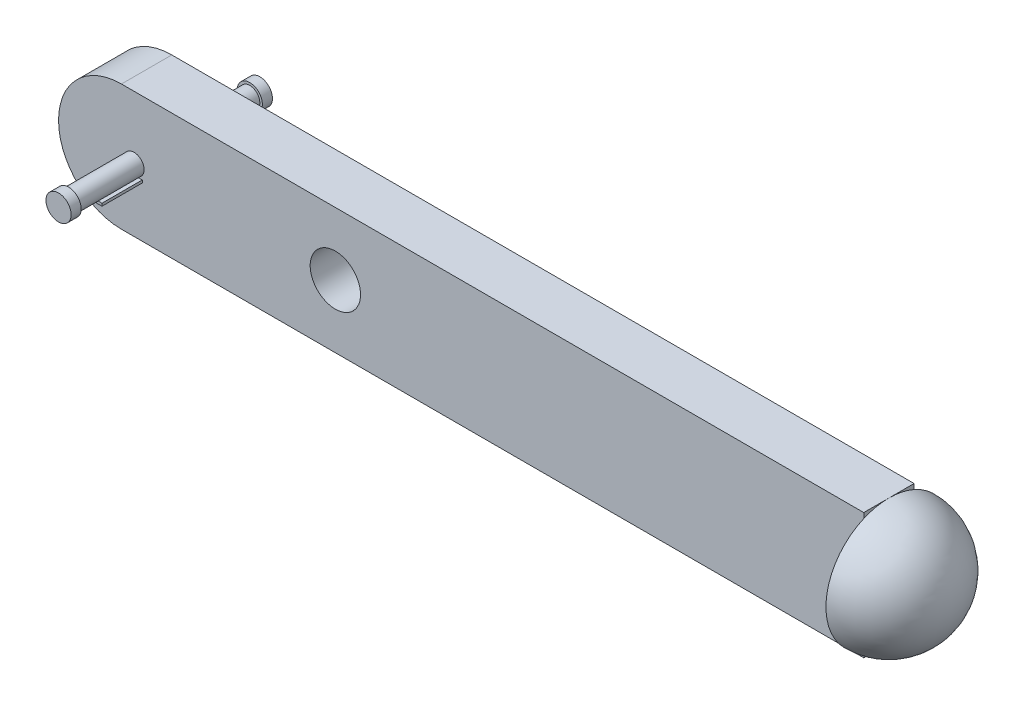
SolidWorks part; units mm, degrees
material "PVC Rigid"
ref_plane "Front Plane" through (0, 0, 0) normal (0, 0, 1) x (1, 0, 0)
ref_plane "Top Plane" through (0, 0, 0) normal (0, 1, 0) x (1, 0, 0)
ref_plane "Right Plane" through (0, 0, 0) normal (1, 0, 0) x (0, 0, -1)
sketch "Sketch1" plane through (0, 0, 0) normal (0, 0, 1) x (1, 0, 0)
  line L0 (16.513, -9.9849) -> (16.513, -41.7349)
  line L1 (-170.812, -9.9849) -> (16.513, -9.9849)
  line L3 (-170.812, -41.7349) -> (16.513, -41.7349)
  arc A0 (-170.812, -9.9849) -> (-170.812, -41.7349) centre (-170.812, -25.8599) ccw
  circle A2 centre (-116.837, -25.8599) radius 6.35
  point P5 (-186.687, -25.8599)
  dimension "D1" = 133.35
  dimension "D3" = 203.2
  dimension "D2" = 31.75
extrude "Boss-Extrude1" add sketch "Sketch1" along normal blind 12.7
sketch "Sketch2" plane through (0, 0, 12.7) normal (0, 0, 1) x (1, 0, 0)
  line L0 (-170.812, -41.7349) -> (16.513, -41.7349) construction
  circle A0 centre (-167.637, -25.8599) radius 3.175
  arc A1 (-170.812, -9.9849) -> (-170.812, -41.7349) centre (-170.812, -25.8599) ccw construction
  point P7 (-186.687, -25.8599)
  dimension "D1" = 15.875
  dimension "D3" = 6.35
  dimension "D2" = 19.05
extrude "Boss-Extrude2" add sketch "Sketch2" along normal blind 19.05 and the other way blind 31.75
sketch "Sketch3" plane through (0, 0, 31.75) normal (0, 0, 1) x (1, 0, 0)
  circle A0 centre (-167.637, -25.8599) radius 2.54
  dimension "D1" = 5.08
extrude "Cut-Extrude1" cut sketch "Sketch3" along direction (0, 0, 1) on the side against the normal up to surface (16.51 mm away) from offset 2.54 flip side to cut offset against normal yes
sketch "Sketch4" plane through (0, 0, -19.05) normal (0, 0, -1) x (-1, 0, 0)
  circle A0 centre (167.637, -25.8599) radius 2.54
  dimension "D1" = 5.08
extrude "Cut-Extrude2" cut sketch "Sketch4" along direction (0, 0, 1) on the side against the normal up to surface (16.51 mm away) from offset 2.54 flip side to cut contours A0 offset against normal yes
sketch "Sketch6" plane through (16.513, 0, 0) normal (1, 0, 0) x (0, 0, -1)
  line L0 (-6.35, -9.9849) -> (-6.35, -41.7349)
  line L1 (-12.7, -9.9849) -> (0, -9.9849) construction
  line L2 (-12.7, -41.7349) -> (0, -41.7349) construction
  arc A0 (-6.35, -9.9849) -> (-6.35, -41.7349) centre (-6.3705, -25.8599) ccw
revolve "Revolve1" add sketch "Sketch6" angle 180 about L0
sketch "Sketch9" plane through (0, 0, 12.7) normal (0, 0, 1) x (1, 0, 0)
  line L1 (-169.6267, -28.3342) -> (-165.5648, -28.3342)
  line L2 (-169.6267, -28.3342) -> (-169.6267, -28.9947)
  line L3 (-169.6267, -28.9947) -> (-165.5648, -28.9947)
  line L4 (-165.5648, -28.3342) -> (-165.5648, -28.9947)
  circle A0 centre (-167.637, -25.8599) radius 3.175 construction
extrude "Boss-Extrude4" add sketch "Sketch9" along normal blind 10.16
